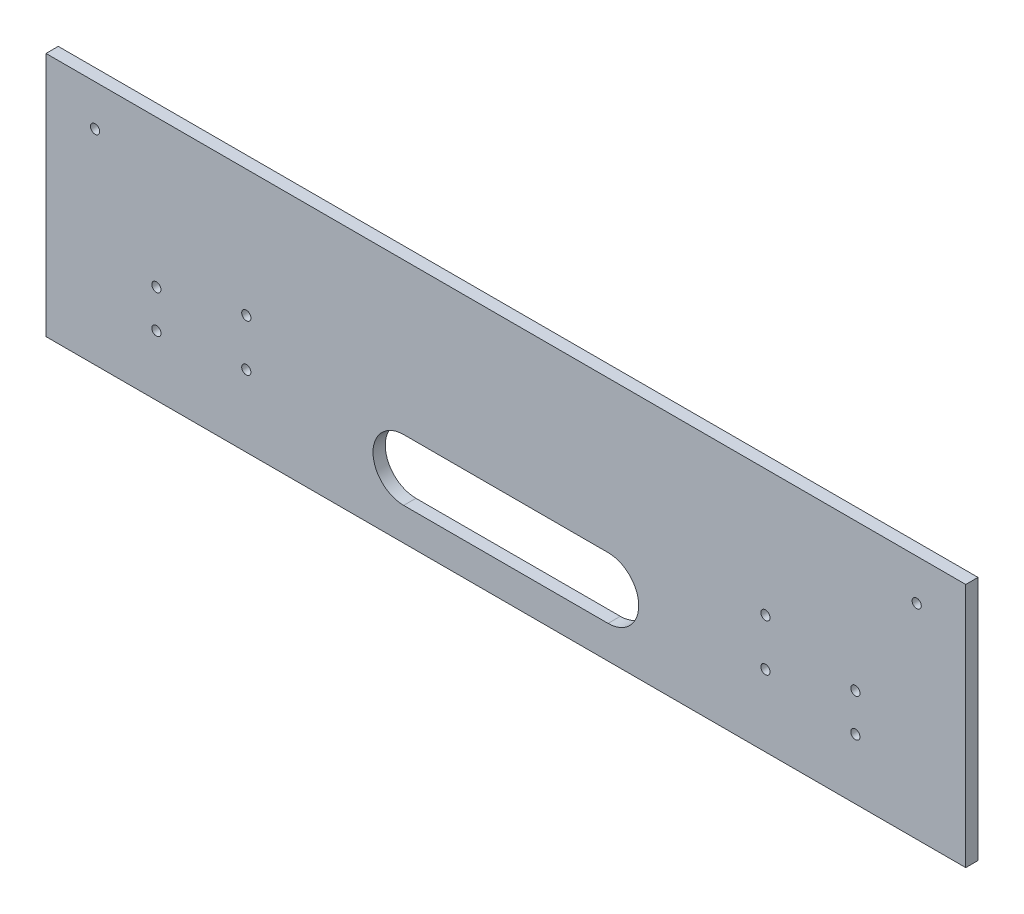
SolidWorks part; units mm, degrees
material "Pino"
ref_plane "Piano frontale" through (0, 0, 0) normal (0, 0, 1) x (1, 0, 0)
ref_plane "Piano superiore" through (0, 0, 0) normal (0, 1, 0) x (1, 0, 0)
ref_plane "Piano destro" through (0, 0, 0) normal (1, 0, 0) x (0, 0, -1)
sketch "Schizzo1" plane through (0, 0, 0) normal (0, 0, 1) x (1, 0, 0)
  line L1 (-225, 60) -> (225, 60)
  line L2 (-225, 60) -> (-225, -60)
  line L3 (-225, -60) -> (225, -60)
  line L4 (225, 60) -> (225, -60)
  line L5 (-225, 60) -> (225, -60) construction
  line L6 (-225, -60) -> (225, 60) construction
  point P4 (0, 0)
  dimension "D1" = 120
  dimension "D2" = 450
extrude "Estrusione-Estrusione1" add sketch "Schizzo1" along normal blind 6
sketch "Schizzo2" plane through (0, 0, 6) normal (0, 0, 1) x (1, 0, 0)
  line L0 (-50, -29) -> (50, -29) construction
  line L5 (0, -29) -> (0, 0) construction
  line L6 (-225, -60) -> (225, -60) construction
  line L7 (-50, -14) -> (50, -14)
  line L8 (-50, -44) -> (50, -44)
  arc A0 (-50, -14) -> (-50, -44) centre (-50, -29) ccw
  arc A1 (50, -44) -> (50, -14) centre (50, -29) ccw
  point P11 (0, -29)
  dimension "D1" = 130
  dimension "D2" = 30
  dimension "D4" = 16
extrude "Taglio-Estrusione1" cut sketch "Schizzo2" against normal blind 10
sketch "Schizzo3" plane through (0, 0, 0) normal (0, 0, -1) x (-1, 0, 0)
  line L0 (-127, -2) -> (-127, -25) construction
  line L1 (127, -2) -> (127, -25) construction
  line L2 (-225, -60) -> (-225, 60) construction
  line L3 (225, -60) -> (-225, -60) construction
  line L4 (225, 60) -> (225, -60) construction
  circle A0 centre (-171, -12) radius 2.25
  circle A1 centre (-171, -30.5) radius 2.25
  circle A2 centre (171, -12) radius 2.25
  circle A3 centre (171, -30.5) radius 2.25
  circle A5 centre (201, 40) radius 2.25
  circle A7 centre (-201, 40) radius 2.25
  circle A8 centre (-127, -2) radius 2.25
  circle A9 centre (-127, -25) radius 2.25
  circle A10 centre (127, -2) radius 2.25
  circle A11 centre (127, -25) radius 2.25
  dimension "D1" = 4.5
  dimension "D2" = 23
  dimension "D3" = 98
  dimension "D4" = 58
  dimension "D5" = 98
  dimension "D6" = 58
extrude "Taglio-Estrusione2" cut sketch "Schizzo3" against normal blind 10
